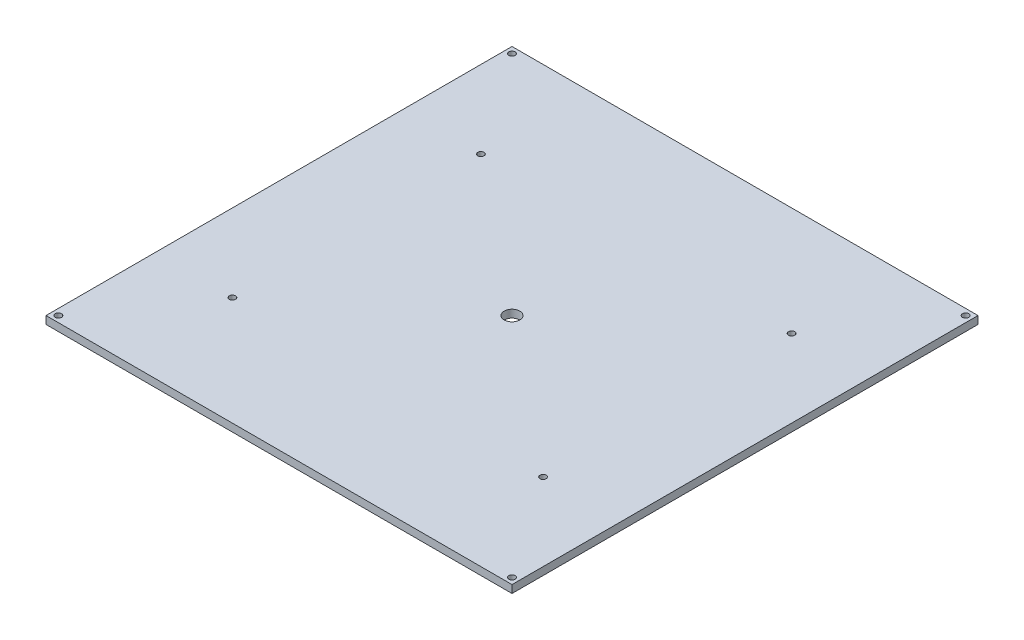
SolidWorks part; units mm, degrees
ref_plane "Front Plane" through (0, 0, 0) normal (0, 0, 1) x (1, 0, 0)
ref_plane "Top Plane" through (0, 0, 0) normal (0, 1, 0) x (1, 0, 0)
ref_plane "Right Plane" through (0, 0, 0) normal (1, 0, 0) x (0, 0, -1)
sketch "Sketch1" plane through (0, 0, 0) normal (0, 1, 0) x (1, 0, 0)
  line L1 (150, -150) -> (-150, -150)
  line L2 (150, -150) -> (150, 150)
  line L3 (150, 150) -> (-150, 150)
  line L4 (-150, -150) -> (-150, 150)
  line L5 (150, -150) -> (-150, 150) construction
  line L6 (150, 150) -> (-150, -150) construction
  point P0 (0, 0)
  dimension "D1" = 300
  dimension "D2" = 300
extrude "Boss-Extrude1" add sketch "Sketch1" along normal blind 5
sketch "Sketch2" plane through (0, 5, 0) normal (0, 1, 0) x (1, 0, 0)
  line L0 (150, 150) -> (-150, 150) construction
  line L2 (-150, 150) -> (-150, -150) construction
  line L3 (0, 0) -> (0, 49.0083) construction
  line L4 (0, 0) -> (-34.9845, 0) construction
  circle A0 centre (-146, 146) radius 2.05
  dimension "D3" = 4.1
  dimension "D1" = 4
  dimension "D2" = 4
extrude "Cut-Extrude1" cut sketch "Sketch2" against normal up to next
mirror "Mirror1" about plane through (0, 0, 0) normal (1, 0, 0) of "Cut-Extrude1" second plane through (0, 0, 0) second plane normal (0, 0, 1)
sketch "Sketch3" plane through (0, 5, 0) normal (0, 1, 0) x (1, 0, 0)
  line L1 (-100, -80) -> (100, -80) construction
  line L2 (-100, -80) -> (-100, 80) construction
  line L3 (-100, 80) -> (100, 80) construction
  line L4 (100, -80) -> (100, 80) construction
  line L5 (-100, -80) -> (100, 80) construction
  line L6 (-100, 80) -> (100, -80) construction
  circle A0 centre (-100, 80) radius 2
  circle A1 centre (100, 80) radius 2
  circle A2 centre (100, -80) radius 2
  circle A3 centre (-100, -80) radius 2
  circle A4 centre (0, 0) radius 5
  point P0 (0, 0)
  dimension "D3" = 4
  dimension "D4" = 10
  dimension "D1" = 200
  dimension "D2" = 160
extrude "Cut-Extrude2" cut sketch "Sketch3" against normal up to next
